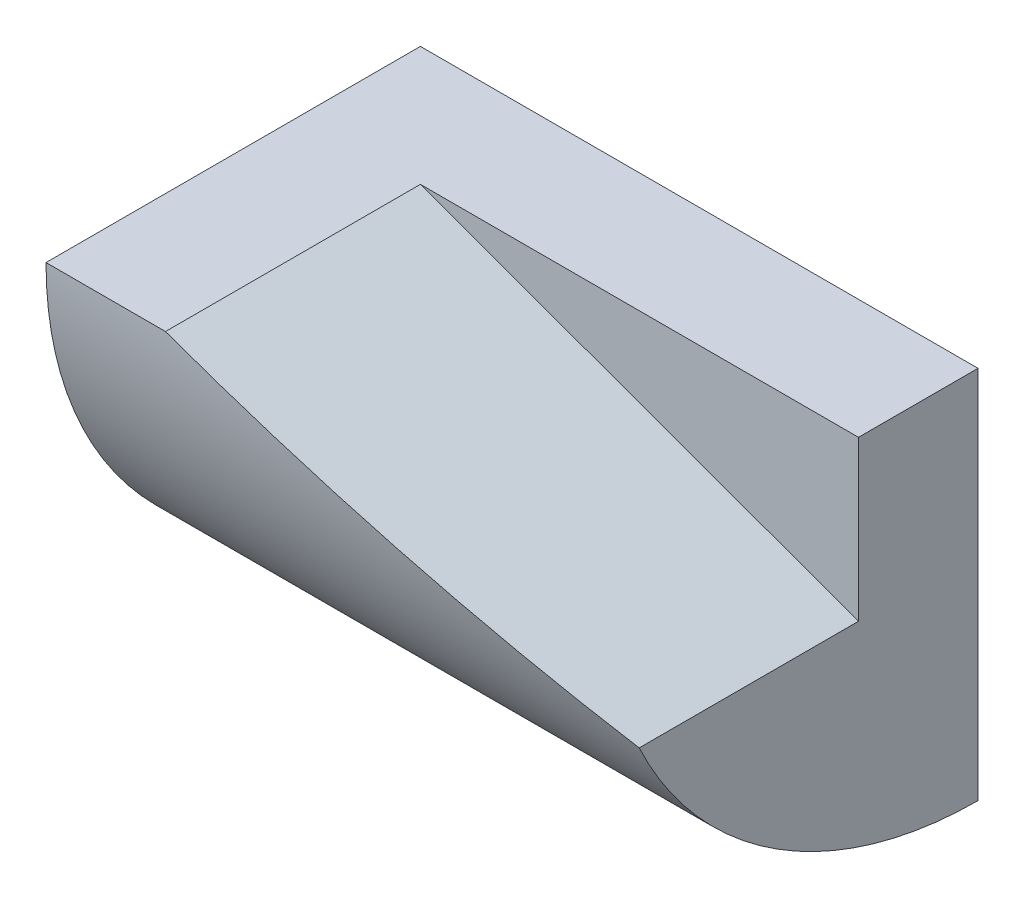
SolidWorks part; units mm, degrees
ref_plane "Front Plane" through (0, 0, 0) normal (0, 0, 1) x (1, 0, 0)
ref_plane "Top Plane" through (0, 0, 0) normal (0, 1, 0) x (1, 0, 0)
ref_plane "Right Plane" through (0, 0, 0) normal (1, 0, 0) x (0, 0, -1)
sketch "Sketch1" plane through (0, 0, 0) normal (1, 0, 0) x (0, 0, -1)
  line L0 (-47, 0) -> (0, 0)
  line L1 (0, 0) -> (0, -47)
  arc A0 (0, -47) -> (-47, 0) centre (0, 0) cw
  point P3 (0, 0)
  dimension "D1" = 47
extrude "Boss-Extrude1" add sketch "Sketch1" along normal blind 70
ref_plane "Plane1" through (0, 0, 47) normal (0, 0, -1) x (-1, 0, 0)
sketch "Sketch3" plane through (0, 0, 47) normal (0, 0, -1) x (-1, 0, 0)
  line L0 (-15, 0) -> (-70, -20)
  line L1 (-70, 0) -> (0, 0) construction
  line L2 (-70, 0) -> (-70, -47) construction
  line L3 (-70, -20) -> (-70, 0)
  line L4 (-70, 0) -> (-15, 0)
  dimension "D1" = 15
  dimension "D2" = 20
extrude "Cut-Extrude2" cut sketch "Sketch3" along normal blind 32 contours L4 L0 L3
